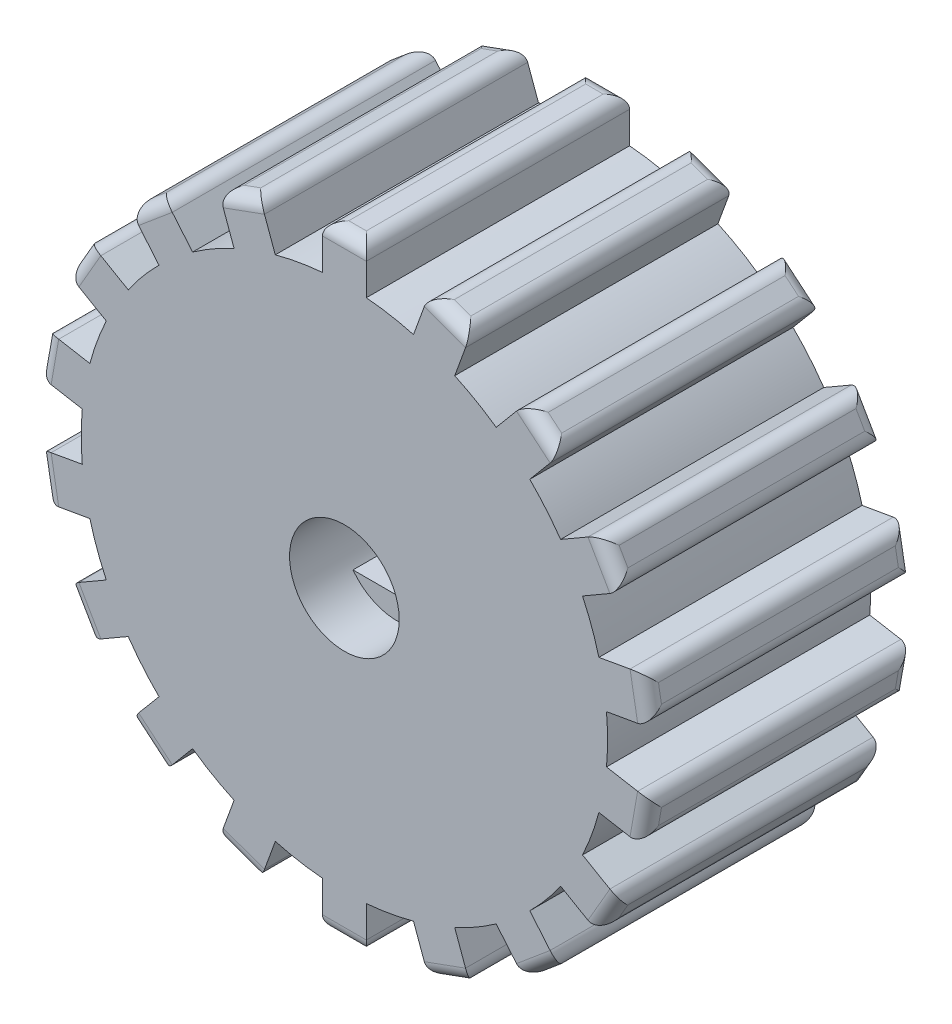
SolidWorks part; units mm, degrees
ref_plane "Front Plane" through (0, 0, 0) normal (0, 0, 1) x (1, 0, 0)
ref_plane "Top Plane" through (0, 0, 0) normal (0, 1, 0) x (1, 0, 0)
ref_plane "Right Plane" through (0, 0, 0) normal (1, 0, 0) x (0, 0, -1)
sketch "Sketch2" plane through (0, 0, 0) normal (0, 0, 1) x (1, 0, 0)
  circle A0 centre (0, 0) radius 60
extrude "Boss-Extrude1" add sketch "Sketch2" along normal blind 60
sketch "Sketch3" plane through (0, 0, 60) normal (0, 0, 1) x (1, 0, 0)
  line L0 (0, 60) -> (0, 70) construction
  line L1 (5, 70) -> (-5, 70)
  line L2 (-5, 70) -> (-5, 59.5215)
  line L3 (-5, 59.5215) -> (5, 59.5215)
  line L4 (5, 59.5215) -> (5, 70)
  circle A0 centre (0, 0) radius 60 construction
  point P9 (0, 70)
extrude "Boss-Extrude2" add sketch "Sketch3" against normal blind 60
fillet "Fillet2" radius 3 4 edges at (-5, 70, 30) (0, 70, 60) (0, 70, 0) (5, 70, 30)
pattern_circular "CirPattern1" count 18 over 360 about axis through (0, 0, 0) along (0, 0, 1) of "Fillet2", "Boss-Extrude2"
sketch "Sketch4" plane through (0, 0, 60) normal (0, 0, 1) x (1, 0, 0)
  circle A0 centre (0, 0) radius 10
extrude "Cut-Extrude1" cut sketch "Sketch4" against normal blind 60
sketch "Sketch5" plane through (0, 0, 60) normal (0, 0, 1) x (1, 0, 0)
  circle A0 centre (0, 0) radius 22.4818
extrude "Boss-Extrude3" add sketch "Sketch5" against normal blind 60
sketch "Sketch6" plane through (0, 0, 60) normal (0, 0, 1) x (1, 0, 0)
  circle A0 centre (0, 0) radius 12.5
extrude "Cut-Extrude2" cut sketch "Sketch6" against normal blind 12
sketch "Sketch7" plane through (0, 0, 48) normal (0, 0, 1) x (1, 0, 0)
  line L1 (10.0373, -7.45) -> (-10.0373, -7.45)
  line L3 (10.0373, 7.45) -> (-10.0373, 7.45)
  arc A0 (-10.0373, 7.45) -> (-10.0373, -7.45) centre (0, 0) ccw
  arc A1 (10.0373, -7.45) -> (10.0373, 7.45) centre (0, 0) ccw
  point P0 (0, 0)
extrude "Cut-Extrude3" cut sketch "Sketch7" against normal blind 30.5
scale "Scale1" scale about centroid uniform scaling yes scale factor 0.2
